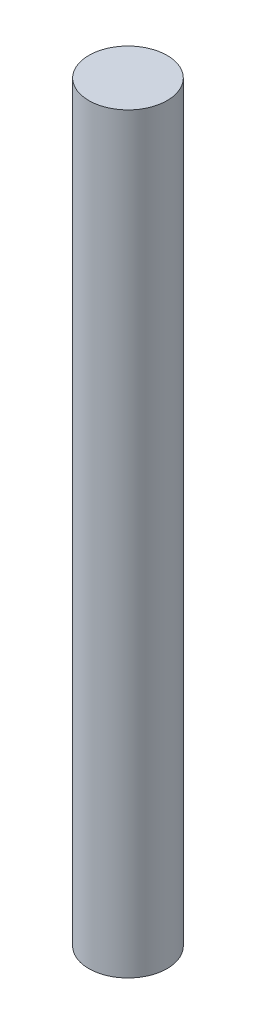
SolidWorks part; units mm, degrees
ref_plane "Front Plane" through (0, 0, 0) normal (0, 0, 1) x (1, 0, 0)
ref_plane "Top Plane" through (0, 0, 0) normal (0, 1, 0) x (1, 0, 0)
ref_plane "Right Plane" through (0, 0, 0) normal (1, 0, 0) x (0, 0, -1)
sketch "Sketch1" plane through (0, 0, 0) normal (0, 1, 0) x (1, 0, 0)
  circle A0 centre (0, 0) radius 12.5
  dimension "D1" = 25
extrude "Boss-Extrude1" add sketch "Sketch1" along normal blind 240
